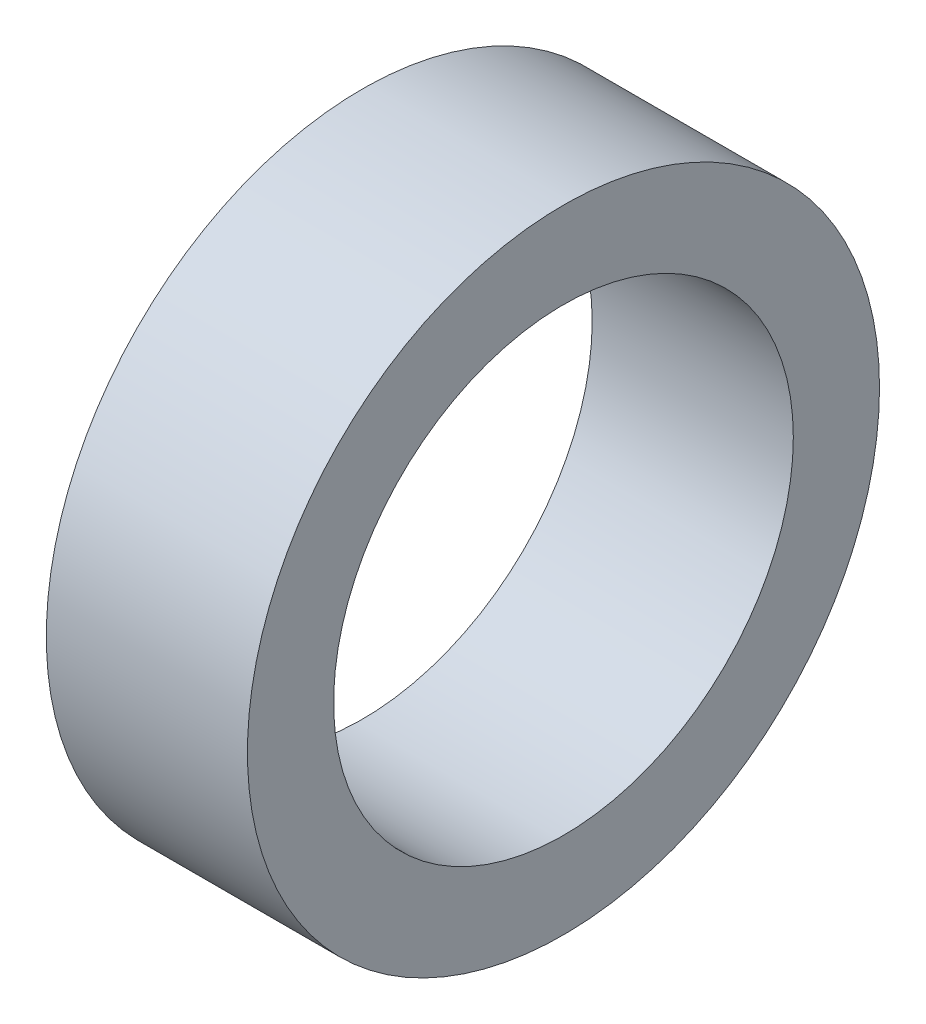
SolidWorks part; units mm, degrees
ref_plane "Front Plane" through (0, 0, 0) normal (1, 0, 0) x (0, 1, 0)
ref_plane "Top Plane" through (0, 0, 0) normal (0, 0, 1) x (0, 1, 0)
ref_plane "Right Plane" through (0, 0, 0) normal (0, 1, 0) x (-1, 0, 0)
sketch "Sketch1" plane through (0, 0, 0) normal (1, 0, 0) x (0, 1, 0)
  circle A0 centre (0, 0) radius 20
  circle A1 centre (0, 0) radius 27.5
  dimension "D1" = 40
  dimension "D2" = 55
extrude "Boss-Extrude1" add sketch "Sketch1" along normal blind 17.5
